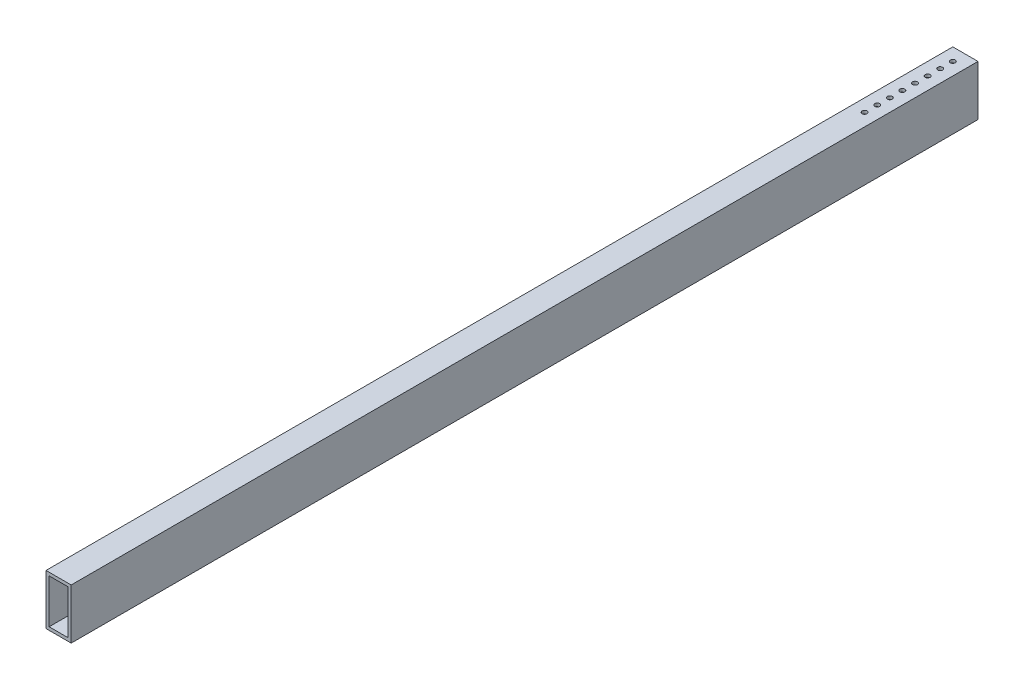
SolidWorks part; units mm, degrees
material "6061-T6 (SS)"
ref_plane "Front Plane" through (0, 0, 0) normal (0, 0, 1) x (1, 0, 0)
ref_plane "Top Plane" through (0, 0, 0) normal (0, 1, 0) x (1, 0, 0)
ref_plane "Right Plane" through (0, 0, 0) normal (1, 0, 0) x (0, 0, -1)
sketch "Sketch1" plane through (0, 0, 0) normal (0, 0, 1) x (1, 0, 0)
  line L0 (-9.525, -22.225) -> (-9.525, 22.225)
  line L1 (-12.7, -25.4) -> (12.7, -25.4)
  line L2 (-12.7, -25.4) -> (-12.7, 25.4)
  line L3 (-12.7, 25.4) -> (12.7, 25.4)
  line L4 (12.7, -25.4) -> (12.7, 25.4)
  line L5 (-12.7, -25.4) -> (12.7, 25.4) construction
  line L6 (-12.7, 25.4) -> (12.7, -25.4) construction
  line L7 (-9.525, 22.225) -> (9.525, 22.225)
  line L8 (9.525, -22.225) -> (9.525, 22.225)
  line L9 (-9.525, -22.225) -> (9.525, -22.225)
  point P0 (0, 0)
  dimension "D1" = 25.4
  dimension "D2" = 50.8
  dimension "D3" = 3.175
extrude "Boss-Extrude1" add sketch "Sketch1" along normal blind 914.4 contours L7 L8 L9 L0
sketch "Sketch2" plane through (0, 25.4, 0) normal (0, 1, 0) x (1, 0, 0)
  line L0 (0, 0) -> (0, -914.4) construction
  line L1 (12.7, -914.4) -> (-12.7, -914.4) construction
  line L2 (12.7, 0) -> (-12.7, 0) construction
  circle A0 centre (0, -12.7) radius 2.4892
  circle A1 centre (0, -25.4) radius 2.4892
  circle A2 centre (0, -38.1) radius 2.4892
  circle A3 centre (0, -50.8) radius 2.4892
  circle A4 centre (0, -63.5) radius 2.4892
  circle A5 centre (0, -76.2) radius 2.4892
  circle A6 centre (0, -88.9) radius 2.4892
  circle A7 centre (0, -101.6) radius 2.4892
  point P9 (0, 0)
  dimension "D1" = 4.9784
  dimension "D2" = 12.7
  dimension "D4" = 12.7
  dimension "D3" = 8
extrude "Cut-Extrude1" cut sketch "Sketch2" against normal through all
